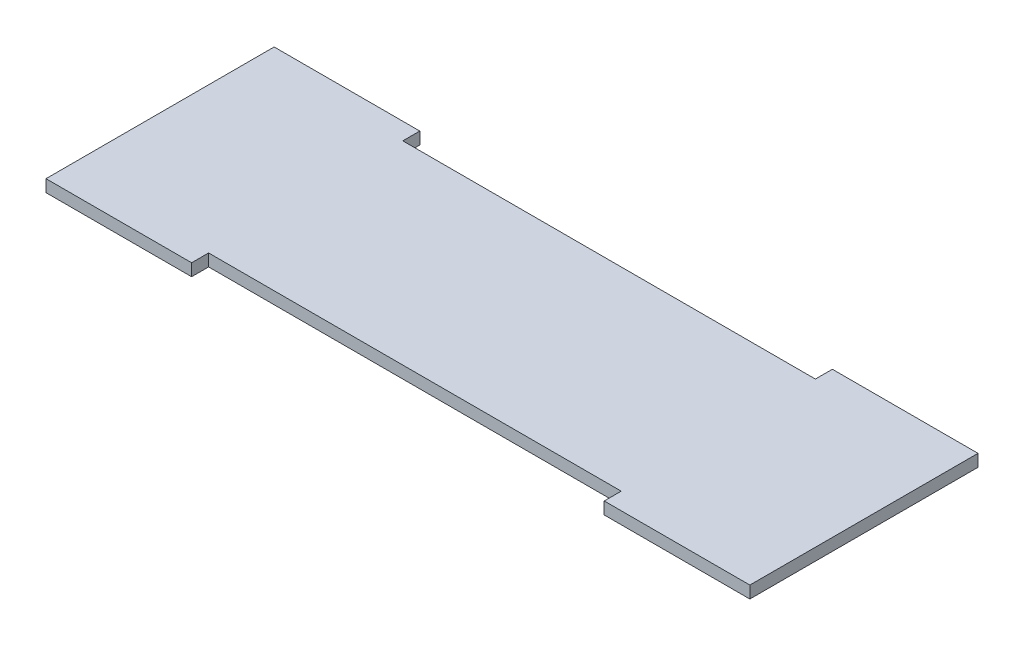
SolidWorks part; units mm, degrees
ref_plane "Front Plane" through (0, 0, 0) normal (0, 0, 1) x (1, 0, 0)
ref_plane "Top Plane" through (0, 0, 0) normal (0, 1, 0) x (1, 0, 0)
ref_plane "Right Plane" through (0, 0, 0) normal (1, 0, 0) x (0, 0, -1)
sketch "Sketch1" plane through (0, 0, 0) normal (0, 1, 0) x (1, 0, 0)
  line L0 (-145, 47) -> (-85, 47)
  line L1 (-85, 47) -> (-85, 40)
  line L2 (-85, 40) -> (85, 40)
  line L3 (85, 40) -> (85, 47)
  line L4 (85, 47) -> (145, 47)
  line L5 (145, 47) -> (145, -47)
  line L6 (145, -47) -> (85, -47)
  line L7 (85, -47) -> (85, -40)
  line L8 (85, -40) -> (-85, -40)
  line L9 (-85, -40) -> (-85, -47)
  line L10 (-85, -47) -> (-145, -47)
  line L11 (-145, -47) -> (-145, 47)
  line L12 (-85, 40) -> (85, -40) construction
  dimension "D1" = 94
extrude "Boss-Extrude1" add sketch "Sketch1" along normal blind 5
